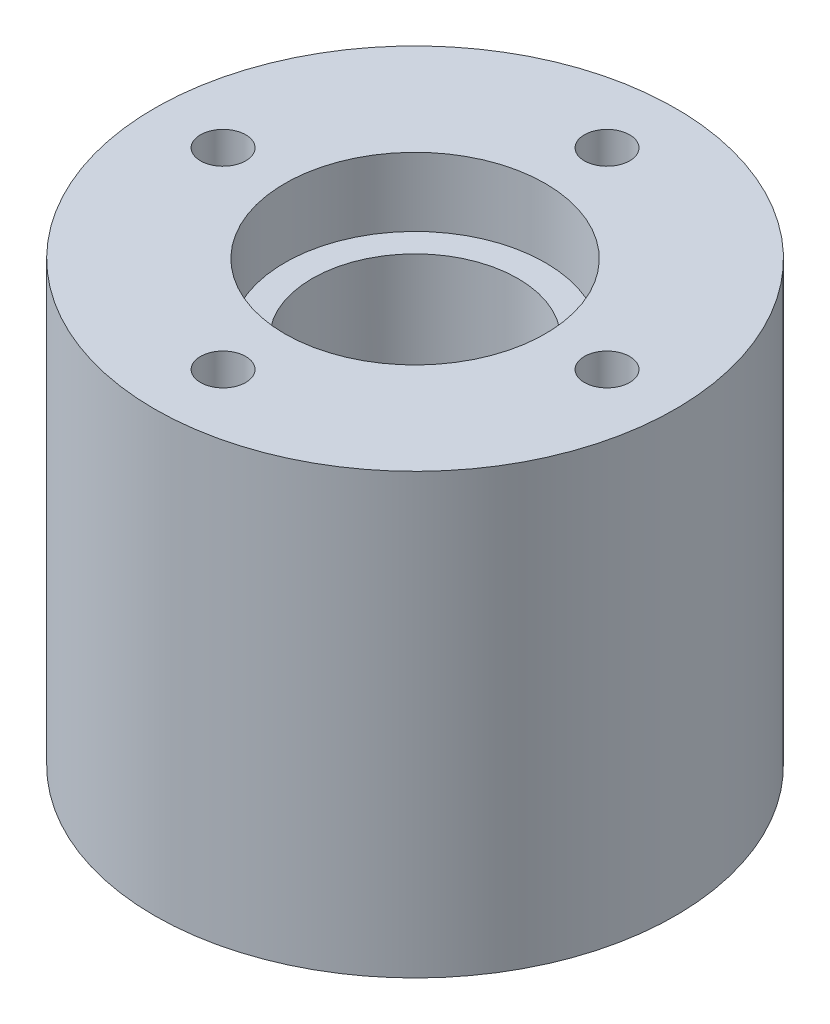
SolidWorks part; units mm, degrees
material "SKD11淬火HRC56-60"
ref_plane "前基準面" through (0, 0, 0) normal (0, 0, 1) x (1, 0, 0)
ref_plane "上基準面" through (0, 0, 0) normal (0, 1, 0) x (1, 0, 0)
ref_plane "右基準面" through (0, 0, 0) normal (1, 0, 0) x (0, 0, -1)
sketch "草图1" plane through (0, 0, 0) normal (0, 1, 0) x (1, 0, 0)
  circle A0 centre (0, 0) radius 19
  circle A1 centre (0, 0) radius 7.5
  dimension "D1" = 15
  dimension "D2" = 38
extrude "凸台-拉伸1" add sketch "草图1" along normal blind 32
sketch "草图2" plane through (0, 32, 0) normal (0, 1, 0) x (1, 0, 0)
  circle A0 centre (0, 0) radius 9.5
  dimension "D1" = 19
extrude "切除-拉伸1" cut sketch "草图2" against normal blind 5
sketch "草图3" plane through (0, 0, 0) normal (0, -1, 0) x (1, 0, 0)
  circle A0 centre (0, 0) radius 9.5
  dimension "D1" = 19
extrude "切除-拉伸2" cut sketch "草图3" against normal blind 5
hole_wizard "M4 螺纹孔1" positions "草图5" profile "草图4" tap size "M4" standard "ISO"
sketch "草图5" plane through (0, 0, 0) normal (0, -1, 0) x (1, 0, 0)
  line L0 (0, 0) -> (22.7796, 0) construction
  line L1 (0, 0) -> (0, -21.0782) construction
  line L2 (0, 0) -> (-21.7084, 0) construction
  line L3 (0, 0) -> (0, 25.6432) construction
  circle A0 centre (0, 0) radius 14 construction
  point P0 (0, -14)
  point P24 (-14, 0)
  point P26 (0, 14)
  point P28 (14, 0)
  dimension "D1" = 28
sketch "草图4" plane through (0, 0, -14) normal (1, 0, 0) x (0, 0, -1)
  line L0 (0, 0) -> (0, 11.0914)
  line L1 (0, 11.0914) -> (1.65, 10.1)
  line L2 (1.65, 10.1) -> (1.65, 0)
  line L5 (1.65, 0) -> (0, 0)
  line L10 (0, 11.0914) -> (-1.65, 10.1) construction
  line L11 (0, -6.35) -> (0, 107.95) construction
  dimension "螺纹孔钻头直径" = 3.3
  dimension "螺纹孔钻头深度" = 10.1
  dimension "导头角度" = 118
cosmetic thread "孔螺蚊线1" parameters "D1"=8, "D2"=4
cosmetic thread "孔螺蚊线2" parameters "D1"=8, "D2"=4
cosmetic thread "孔螺蚊线3" parameters "D1"=8, "D2"=4
cosmetic thread "孔螺蚊线4" parameters "D1"=8, "D2"=4
hole_wizard "M4 螺纹孔2" positions "草图7" profile "草图6" tap size "M4" standard "ISO"
sketch "草图7" plane through (0, 32, 0) normal (0, 1, 0) x (-1, 0, 0)
  line L0 (0, 0) -> (-24.418, 0) construction
  line L1 (0, 0) -> (0, 23.4655) construction
  line L2 (0, 0) -> (36.5321, 0) construction
  line L3 (0, 0) -> (0, -25.9699) construction
  circle A0 centre (0, 0) radius 14 construction
  point P0 (-14, 0)
  point P20 (0, 14)
  point P22 (14, 0)
  point P24 (0, -14)
  dimension "D1" = 28
sketch "草图6" plane through (14, 32, 0) normal (1, 0, 0) x (0, 0, 1)
  line L0 (0, 0) -> (0, 11.0914)
  line L1 (0, 11.0914) -> (1.65, 10.1)
  line L2 (1.65, 10.1) -> (1.65, 0)
  line L5 (1.65, 0) -> (0, 0)
  line L10 (0, 11.0914) -> (-1.65, 10.1) construction
  line L11 (0, -6.35) -> (0, 107.95) construction
  dimension "螺纹孔钻头直径" = 3.3
  dimension "螺纹孔钻头深度" = 10.1
  dimension "导头角度" = 118
cosmetic thread "孔螺蚊线5" parameters "D1"=8, "D2"=4
cosmetic thread "孔螺蚊线6" parameters "D1"=8, "D2"=4
cosmetic thread "孔螺蚊线7" parameters "D1"=8, "D2"=4
cosmetic thread "孔螺蚊线8" parameters "D1"=8, "D2"=4
